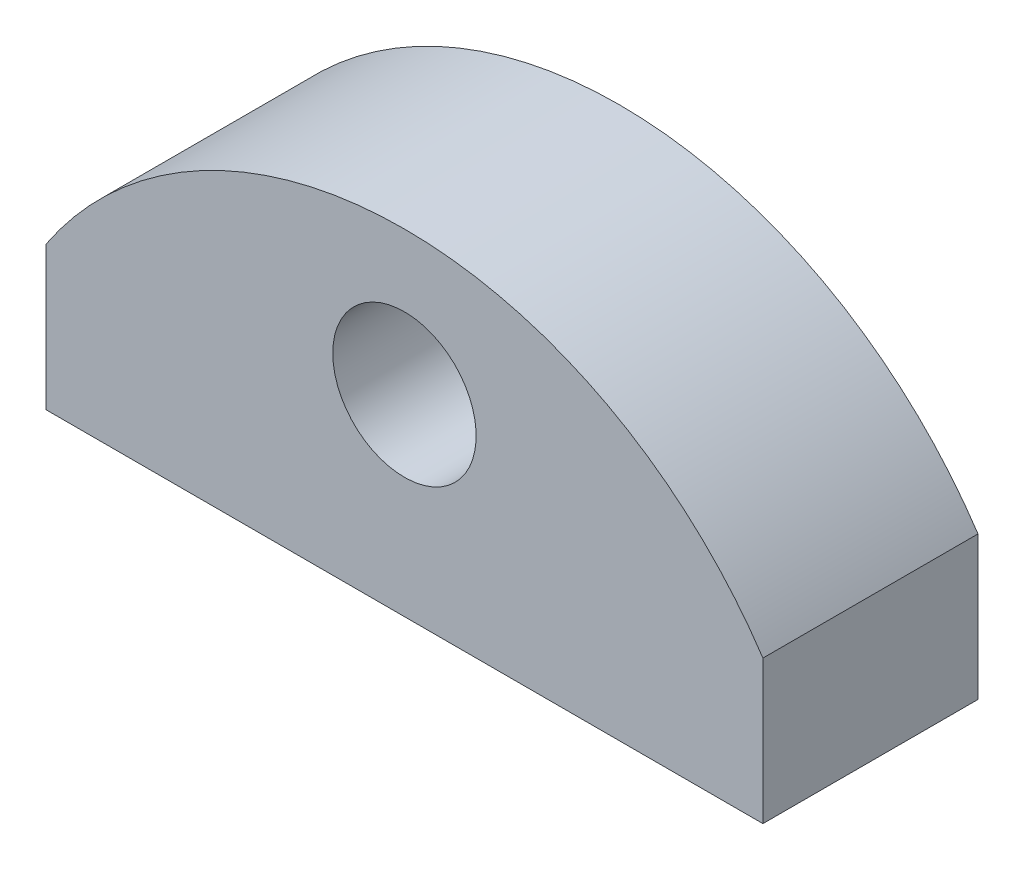
SolidWorks part; units mm, degrees
ref_plane "Front Plane" through (0, 0, 0) normal (0, 0, 1) x (1, 0, 0)
ref_plane "Top Plane" through (0, 0, 0) normal (0, 1, 0) x (1, 0, 0)
ref_plane "Right Plane" through (0, 0, 0) normal (1, 0, 0) x (0, 0, -1)
sketch "Sketch1" plane through (0, 0, 0) normal (0, 0, 1) x (1, 0, 0)
  line L0 (-25, 0) -> (25, 0) construction
  line L1 (-25, 0) -> (-25, -10)
  line L2 (-25, -10) -> (25, -10)
  line L3 (25, -10) -> (25, 0)
  arc A0 (-25, 0) -> (25, 0) centre (0, -16.5831) cw
  point P3 (0, 0)
  dimension "D3" = 30
  dimension "D1" = 50
  dimension "D2" = 10
extrude "Boss-Extrude1" add sketch "Sketch1" along normal blind 15
sketch "Sketch2" plane through (0, 0, 0) normal (0, 0, -1) x (-1, 0, 0)
  line L3 (-25, 0) -> (-25, -10)
  line L4 (-25, -10) -> (25, -10)
  line L5 (25, -10) -> (25, 0)
  line L6 (-25, 0) -> (-25, -10)
  line L7 (-25, -10) -> (25, -10)
  line L8 (25, -10) -> (25, 0)
  circle A0 centre (0, 3.4169) radius 5
  arc A1 (25, 0) -> (-25, 0) centre (0, -16.5831) ccw
  arc A2 (25, 0) -> (-25, 0) centre (0, -16.5831) ccw
  point P7 (0, 0)
  point P8 (0, 0)
  dimension "D2" = 10
  dimension "D3" = 20
  dimension "D1" = 0
extrude "Cut-Extrude1" cut sketch "Sketch2" against normal up to next contours A0
